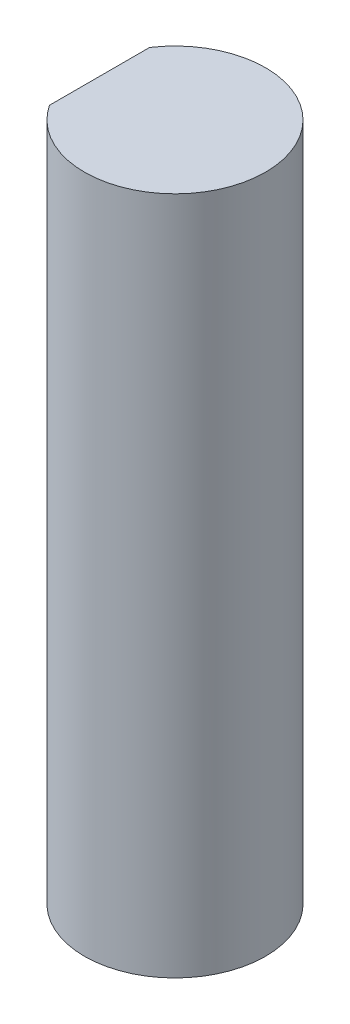
SolidWorks part; units mm, degrees
ref_plane "前视基准面" through (0, 0, 0) normal (0, 0, 1) x (1, 0, 0)
ref_plane "上视基准面" through (0, 0, 0) normal (0, 1, 0) x (1, 0, 0)
ref_plane "右视基准面" through (0, 0, 0) normal (1, 0, 0) x (0, 0, -1)
sketch "草图1" plane through (0, 0, 0) normal (0, 1, 0) x (1, 0, 0)
  circle A0 centre (0, 0) radius 3
  dimension "D1" = 6
extrude "凸台-拉伸1" add sketch "草图1" along normal blind 22.5
sketch "草图3" plane through (0, 22.5, 0) normal (0, 1, 0) x (1, 0, 0)
  line L0 (0, -3.8818) -> (0, 4.3994) construction
  line L1 (-2.5, -1.6583) -> (-2.5, 1.6583)
  circle A0 centre (0, 0) radius 3 construction
  arc A1 (-2.5, 1.6583) -> (-2.5, -1.6583) centre (0, 0) ccw
  point P8 (-3, 0)
  point P9 (-2.5, 0)
  dimension "D1" = 0.5
extrude "切除-拉伸1" cut sketch "草图3" against normal blind 10
